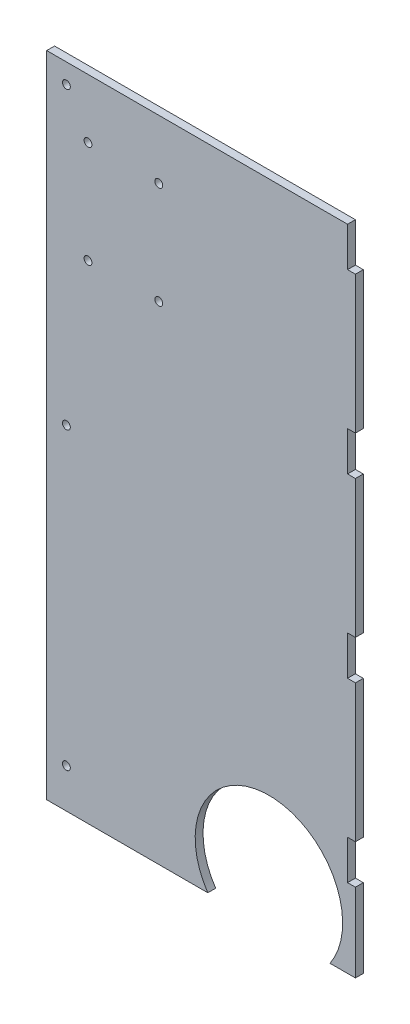
SolidWorks part; units mm, degrees
ref_plane "Front Plane" through (0, 0, 0) normal (0, 0, 1) x (1, 0, 0)
ref_plane "Top Plane" through (0, 0, 0) normal (0, 1, 0) x (1, 0, 0)
ref_plane "Right Plane" through (0, 0, 0) normal (1, 0, 0) x (0, 0, -1)
sketch "Sketch1" plane through (0, 0, 0) normal (0, 0, 1) x (1, 0, 0)
  line L1 (-75, 150) -> (90, 150)
  line L2 (-75, 150) -> (-75, -180)
  line L3 (-75, -180) -> (90, -180)
  line L4 (90, 150) -> (90, -180)
  line L5 (-75, 150) -> (90, -180) construction
  line L6 (-75, -180) -> (90, 150) construction
  point P0 (0, 0)
  dimension "D1" = 165
extrude "Boss-Extrude1" add sketch "Sketch1" along normal blind 4
sketch "Sketch2" plane through (0, 0, 4) normal (0, 0, 1) x (1, 0, 0)
  circle A0 centre (38, -159) radius 37.5
  dimension "D1" = 75
extrude "Cut-Extrude1" cut sketch "Sketch2" against normal through all
sketch "Sketch4" plane through (0, 0, 0) normal (0, 0, -1) x (-1, 0, 0)
  line L1 (-90, 150) -> (-82, 150)
  line L2 (-90, 150) -> (-90, -150)
  line L3 (-90, -150) -> (-82, -150)
  line L4 (-82, 150) -> (-82, -150)
  dimension "D1" = 8
extrude "Cut-Extrude3" cut sketch "Sketch4" against normal through all
sketch "Sketch3" plane through (0, 0, 0) normal (0, 0, -1) x (-1, 0, 0)
  line L0 (-78, 150) -> (-78, 130)
  line L1 (-82, 150) -> (75, 150) construction
  line L2 (-78, 130) -> (-82, 130)
  line L4 (-78, 150) -> (-82, 150)
  line L5 (-82, 150) -> (-82, 130)
  line L6 (-78, 60) -> (-82, 60)
  line L7 (-78, 60) -> (-78, 40)
  line L8 (-78, 40) -> (-82, 40)
  line L9 (-82, 60) -> (-82, 40)
  line L10 (-78, -30) -> (-82, -30)
  line L11 (-78, -30) -> (-78, -50)
  line L12 (-78, -50) -> (-82, -50)
  line L13 (-82, -30) -> (-82, -50)
  line L14 (-78, -120) -> (-82, -120)
  line L15 (-78, -120) -> (-78, -140)
  line L16 (-78, -140) -> (-82, -140)
  line L17 (-82, -120) -> (-82, -140)
  line L18 (-82, -150) -> (-82, 150) construction
  dimension "D1" = 4
  dimension "D2" = 20
  dimension "D3" = 4
extrude "Cut-Extrude2" cut sketch "Sketch3" against normal through all
sketch "Sketch5" plane through (0, 0, 4) normal (0, 0, 1) x (1, 0, 0)
  line L0 (82, -150) -> (82, -180)
  line L1 (69.0685, -180) -> (90, -180) construction
  line L2 (82, -180) -> (90, -180)
  line L3 (90, -180) -> (90, -150)
  line L4 (90, -150) -> (82, -150)
extrude "Cut-Extrude4" cut sketch "Sketch5" against normal through all
sketch "Sketch6" plane through (0, 0, 0) normal (0, 0, -1) x (-1, 0, 0)
  line L0 (-78, 150) -> (75, 150) construction
  line L1 (-82, 60) -> (-82, 130) construction
  circle A0 centre (18, 120) radius 2
  circle A1 centre (54, 120) radius 2
  circle A2 centre (18, 68) radius 2
  circle A3 centre (54, 68) radius 2
  dimension "D1" = 4
  dimension "D2" = 36
  dimension "D3" = 52
  dimension "D4" = 30
  dimension "D5" = 100
extrude "Cut-Extrude5" cut sketch "Sketch6" against normal through all
sketch "Sketch7" plane through (0, 0, 4) normal (0, 0, 1) x (1, 0, 0)
  line L0 (-75, 150) -> (-75, -180) construction
  line L1 (78, 150) -> (-75, 150) construction
  circle A0 centre (-65, 140) radius 2
  circle A1 centre (-65, -10) radius 2
  circle A2 centre (-65, -160) radius 2
  dimension "D2" = 4
  dimension "D1" = 10
  dimension "D3" = 10
  dimension "D4" = 3
extrude "Cut-Extrude6" cut sketch "Sketch7" against normal through all
